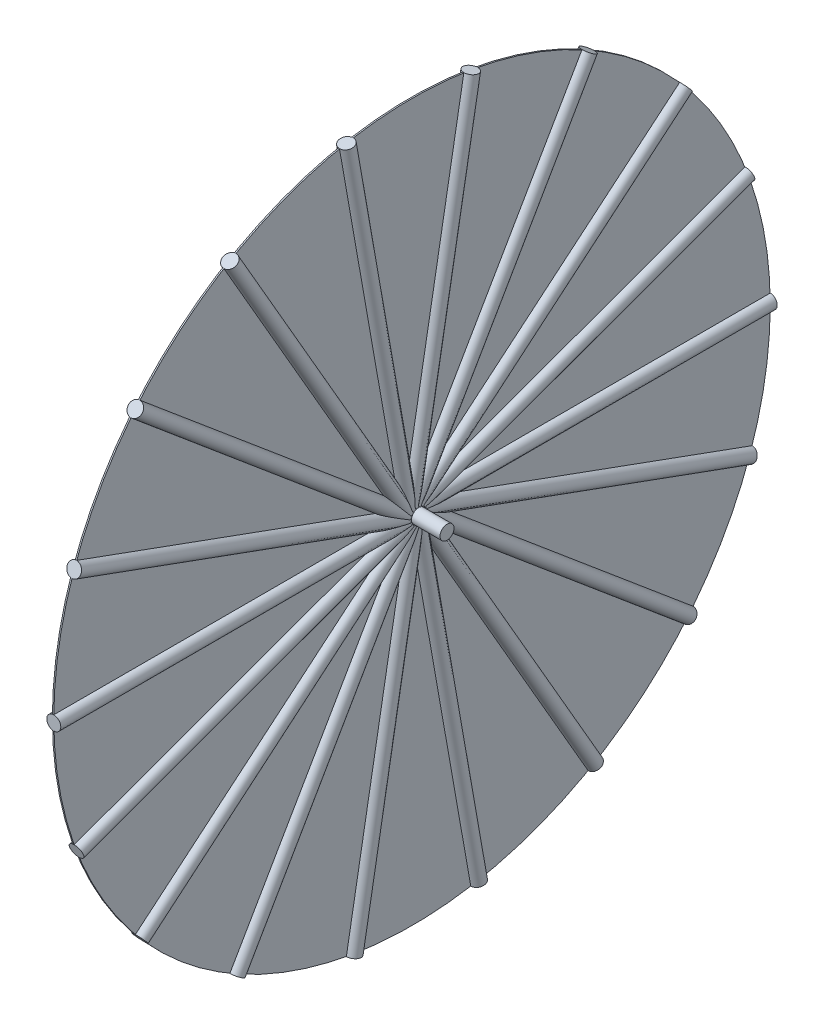
SolidWorks part; units mm, degrees
material "Glass"
ref_plane "Front Plane" through (0, 0, 0) normal (0, 0, 1) x (1, 0, 0)
ref_plane "Top Plane" through (0, 0, 0) normal (0, 1, 0) x (1, 0, 0)
ref_plane "Right Plane" through (0, 0, 0) normal (1, 0, 0) x (0, 0, -1)
sketch "Sketch3" plane through (39.7843, 0, 0) normal (0, 0, 1) x (1, 0, 0)
  line L1 (0, 0) -> (127.0469, 0)
  line L2 (0, 0) -> (0, 25.4)
  line L3 (0, 25.4) -> (127.0469, 25.4)
  line L4 (127.0469, 0) -> (127.0469, 25.4)
revolve "Revolve2" add sketch "Sketch3" angle 360 about L1
sketch "Sketch6" plane through (39.7843, 0, 0) normal (-1, 0, 0) x (0, 0, 1)
  line L1 (25.4, -12.7) -> (1300, -12.7)
  line L2 (25.4, -12.7) -> (25.4, 12.7)
  line L3 (25.4, 12.7) -> (1300, 12.7)
  line L4 (1300, -12.7) -> (1300, 12.7)
revolve "Revolve3" add sketch "Sketch6" angle 360 about L1
sketch "Sketch7" plane through (39.7843, 0, 0) normal (-1, 0, 0) x (0, 0, 1)
  circle A0 centre (0, 0) radius 1300
extrude "Boss-Extrude2" add sketch "Sketch7" along normal blind 5.08
pattern_circular "CirPattern1" count 18 over 360 about axis through (0, 0, 0) along (1, 0, 0) of "Revolve3"
